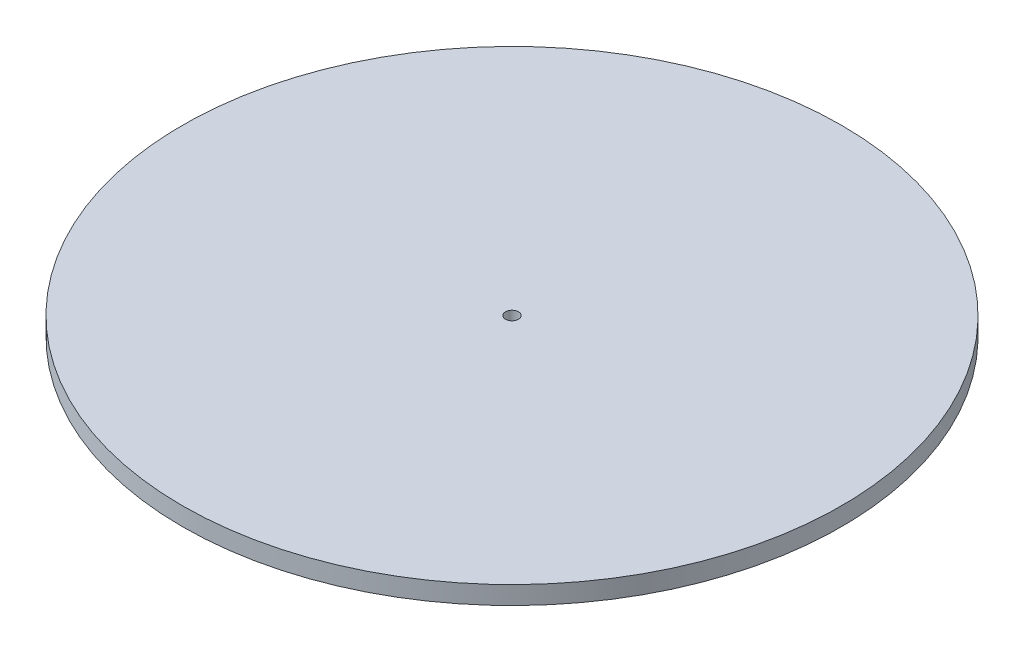
SolidWorks part; units mm, degrees
ref_plane "前视基准面" through (0, 0, 0) normal (0, 0, 1) x (1, 0, 0)
ref_plane "上视基准面" through (0, 0, 0) normal (0, 1, 0) x (1, 0, 0)
ref_plane "右视基准面" through (0, 0, 0) normal (1, 0, 0) x (0, 0, -1)
sketch "草图1" plane through (0, 0, 0) normal (0, 1, 0) x (1, 0, 0)
  circle A2 centre (0, 0) radius 127
  dimension "D1" = 254
extrude "凸台-拉伸1" add sketch "草图1" along normal blind 7
sketch "草图2" plane through (0, 7, 0) normal (0, 1, 0) x (1, 0, 0)
  circle A0 centre (0, 0) radius 2.5
  dimension "D1" = 5
extrude "切除-拉伸1" cut sketch "草图2" against normal up to next
